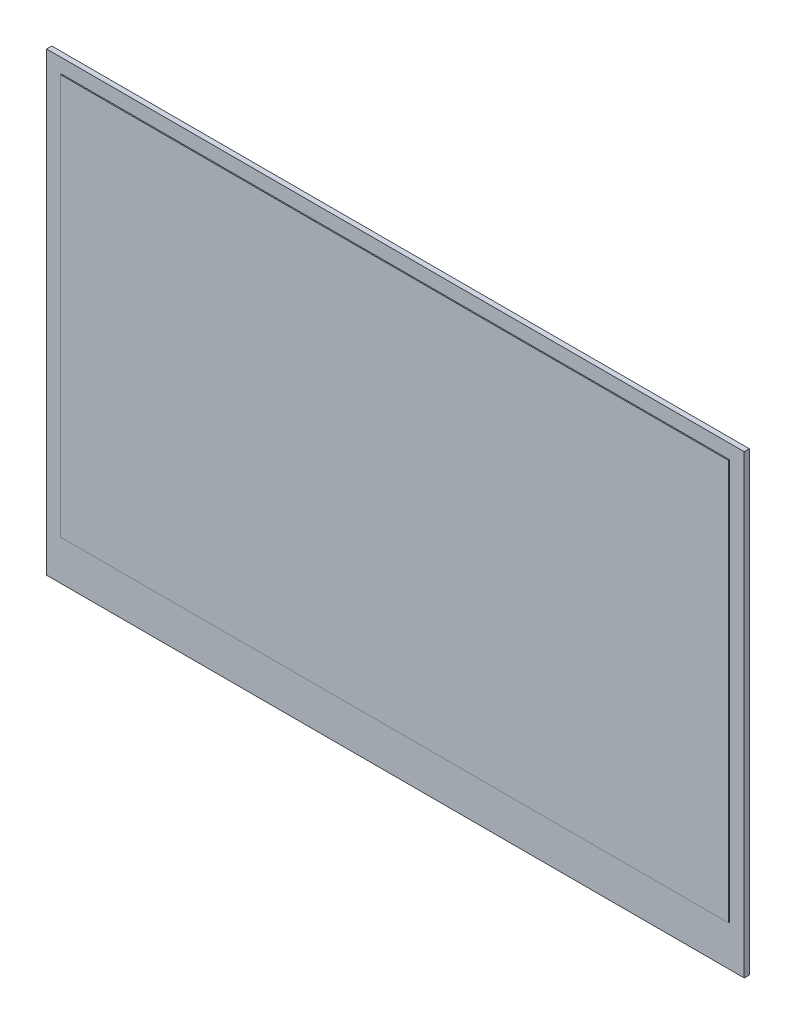
SolidWorks part; units mm, degrees
ref_plane "前视基准面" through (0, 0, 0) normal (0, 0, 1) x (1, 0, 0)
ref_plane "上视基准面" through (0, 0, 0) normal (0, 1, 0) x (1, 0, 0)
ref_plane "右视基准面" through (0, 0, 0) normal (1, 0, 0) x (0, 0, -1)
sketch "草图1" plane through (0, 0, 0) normal (0, 0, 1) x (1, 0, 0)
  line L1 (-85.1, 55.6) -> (85.1, 55.6)
  line L2 (-85.1, 55.6) -> (-85.1, -55.6)
  line L3 (-85.1, -55.6) -> (85.1, -55.6)
  line L4 (85.1, 55.6) -> (85.1, -55.6)
  line L5 (-85.1, 55.6) -> (85.1, -55.6) construction
  line L6 (-85.1, -55.6) -> (85.1, 55.6) construction
  point P0 (0, 0)
  dimension "D1" = 170.2
  dimension "D2" = 111.2
extrude "凸台-拉伸1" add sketch "草图1" along normal blind 1.25
sketch "草图3" plane through (0, 0, 1.25) normal (0, 0, 1) x (1, 0, 0)
  line L0 (85.1, 55.6) -> (-85.1, 55.6) construction
  line L1 (-81.5, 52.11) -> (81.5, 52.11)
  line L2 (-81.5, 52.11) -> (-81.5, -45.61)
  line L3 (-81.5, -45.61) -> (81.5, -45.61)
  line L4 (81.5, 52.11) -> (81.5, -45.61)
  line L5 (-81.5, 52.11) -> (81.5, -45.61) construction
  line L6 (-81.5, -45.61) -> (81.5, 52.11) construction
  line L7 (-85.1, -55.6) -> (85.1, -55.6) construction
  point P0 (0, 3.25)
  point P10 (0, -55.6)
  dimension "D1" = 163
  dimension "D2" = 97.72
  dimension "D3" = 3.49
extrude "凸台-拉伸2" add sketch "草图3" along normal blind 0.25
sketch "草图4" plane through (0, 0, 1.5) normal (0, 0, 1) x (1, 0, 0)
  text T0 "7.5寸电子座牌" font "宋体" height in points 36
